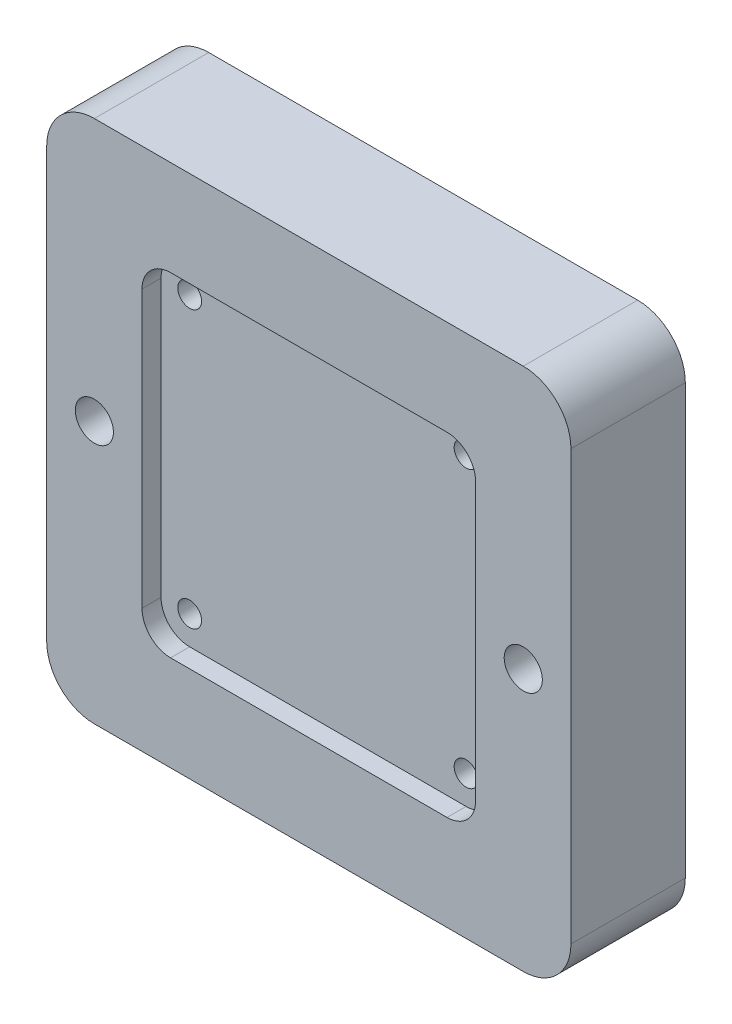
SolidWorks part; units mm, degrees
ref_plane "Front Plane" through (0, 0, 0) normal (0, 0, 1) x (1, 0, 0)
ref_plane "Top Plane" through (0, 0, 0) normal (0, 1, 0) x (1, 0, 0)
ref_plane "Right Plane" through (0, 0, 0) normal (1, 0, 0) x (0, 0, -1)
sketch "Sketch1" plane through (0, 0, 0) normal (0, 0, 1) x (1, 0, 0)
  line L0 (0, 55) -> (0, -55) construction
  line L1 (-45, 55) -> (45, 55)
  line L2 (-55, 45) -> (-55, -45)
  line L3 (-45, -55) -> (45, -55)
  line L4 (55, 45) -> (55, -45)
  line L5 (0, -55) -> (0, -35) construction
  line L6 (0, 35) -> (0, -35) construction
  line L7 (-29, 35) -> (29, 35)
  line L8 (-35, 29) -> (-35, -29)
  line L9 (-29, -35) -> (29, -35)
  line L10 (35, 29) -> (35, -29)
  line L11 (-35, 0) -> (-55, 0) construction
  line L12 (35, 0) -> (55, 0) construction
  arc A0 (45, 55) -> (55, 45) centre (45, 45) cw
  arc A1 (55, -45) -> (45, -55) centre (45, -45) cw
  arc A2 (-45, -55) -> (-55, -45) centre (-45, -45) cw
  arc A3 (-45, 55) -> (-55, 45) centre (-45, 45) ccw
  circle A4 centre (-45, 0) radius 4 construction
  circle A5 centre (45, 0) radius 4 construction
  arc A6 (-35, -29) -> (-29, -35) centre (-29, -29) ccw
  arc A7 (29, -35) -> (35, -29) centre (29, -29) ccw
  arc A8 (35, 29) -> (29, 35) centre (29, 29) ccw
  arc A9 (-29, 35) -> (-35, 29) centre (-29, 29) ccw
  point P31 (111.9206, -20.4692)
  point P32 (45, 0)
  point P39 (-45, 0)
  dimension "D1" = 10
  dimension "D2" = 8
  dimension "D3" = 6
  dimension "D4" = 70
  dimension "D5" = 70
  dimension "D6" = 20
extrude "Boss-Extrude1" add sketch "Sketch1" against normal blind 4
sketch "Sketch2" plane through (0, 0, -4) normal (0, 0, 1) x (1, 0, 0)
  line L8 (-45, -55) -> (45, -55) construction
  line L9 (55, 45) -> (55, -45) construction
  line L10 (-45, 55) -> (45, 55) construction
  line L11 (-55, 45) -> (-55, -45) construction
  line L12 (-45, -55) -> (45, -55)
  line L13 (55, 45) -> (55, -45)
  line L14 (-45, 55) -> (45, 55)
  line L15 (-55, 45) -> (-55, -45)
  arc A8 (45, -55) -> (55, -45) centre (45, -45) ccw construction
  arc A9 (55, 45) -> (45, 55) centre (45, 45) ccw construction
  arc A10 (-45, 55) -> (-55, 45) centre (-45, 45) ccw construction
  arc A11 (-55, -45) -> (-45, -55) centre (-45, -45) ccw construction
  arc A12 (45, -55) -> (55, -45) centre (45, -45) ccw
  arc A13 (55, 45) -> (45, 55) centre (45, 45) ccw
  arc A14 (-45, 55) -> (-55, 45) centre (-45, 45) ccw
  arc A15 (-55, -45) -> (-45, -55) centre (-45, -45) ccw
extrude "Boss-Extrude2" add sketch "Sketch2" against normal blind 20
sketch "Sketch3" plane through (0, 0, 0) normal (0, 0, 1) x (1, 0, 0)
  point P0 (-45, 0)
  point P3 (45, 0)
hole_wizard "Ø8.0mm Dowel Hole1" positions "Sketch3" profile "Sketch4" hole size "Ø8.0" standard "ANSI Metric"
sketch "Sketch4" plane through (-45, 0, 0) normal (1, 0, 0) x (0, -1, 0)
  line L0 (0, 0) -> (0, 20.4034)
  line L1 (0, 20.4034) -> (4, 18)
  line L2 (4, 18) -> (4, 0)
  line L5 (4, 0) -> (0, 0)
  line L10 (0, 20.4034) -> (-4, 18) construction
  line L11 (0, -6.35) -> (0, 107.95) construction
  dimension "Hole Dia." = 8
  dimension "Hole Depth" = 18
  dimension "Drill Angle" = 118
sketch "Sketch5" plane through (0, 0, -4) normal (0, 0, 1) x (1, 0, 0)
  line L0 (-29, 29) -> (29, -29) construction
  line L1 (-29, 29) -> (29, 29) construction
  line L2 (-29, 29) -> (-29, -29) construction
  line L3 (-29, -29) -> (29, -29) construction
  line L4 (29, 29) -> (29, -29) construction
  point P5 (-29, 29)
  point P7 (29, 29)
  point P8 (29, -29)
  point P9 (-29, -29)
  dimension "D1" = 58
sketch "Sketch6" plane through (0, 0, -4) normal (0, 0, 1) x (1, 0, 0)
  point P0 (-29, 29)
  point P3 (29, 29)
  point P6 (29, -29)
  point P9 (-29, -29)
hole_wizard "Tap Drill for M6x1.0 Tap1" positions "Sketch6" profile "Sketch7" hole size "M6x1.0" standard "ANSI Metric"
sketch "Sketch7" plane through (-29, 29, -4) normal (1, 0, 0) x (0, -1, 0)
  line L0 (0, 0) -> (0, 11.5022)
  line L1 (0, 11.5022) -> (2.5, 10)
  line L2 (2.5, 10) -> (2.5, 0)
  line L5 (2.5, 0) -> (0, 0)
  line L10 (0, 11.5022) -> (-2.5, 10) construction
  line L11 (0, -6.35) -> (0, 107.95) construction
  dimension "Hole Dia." = 5
  dimension "Hole Depth" = 10
  dimension "Drill Angle" = 118
sketch "Sketch8" [suppressed] plane through (0, 0, -24) normal (0, 0, -1) x (-1, 0, 0)
